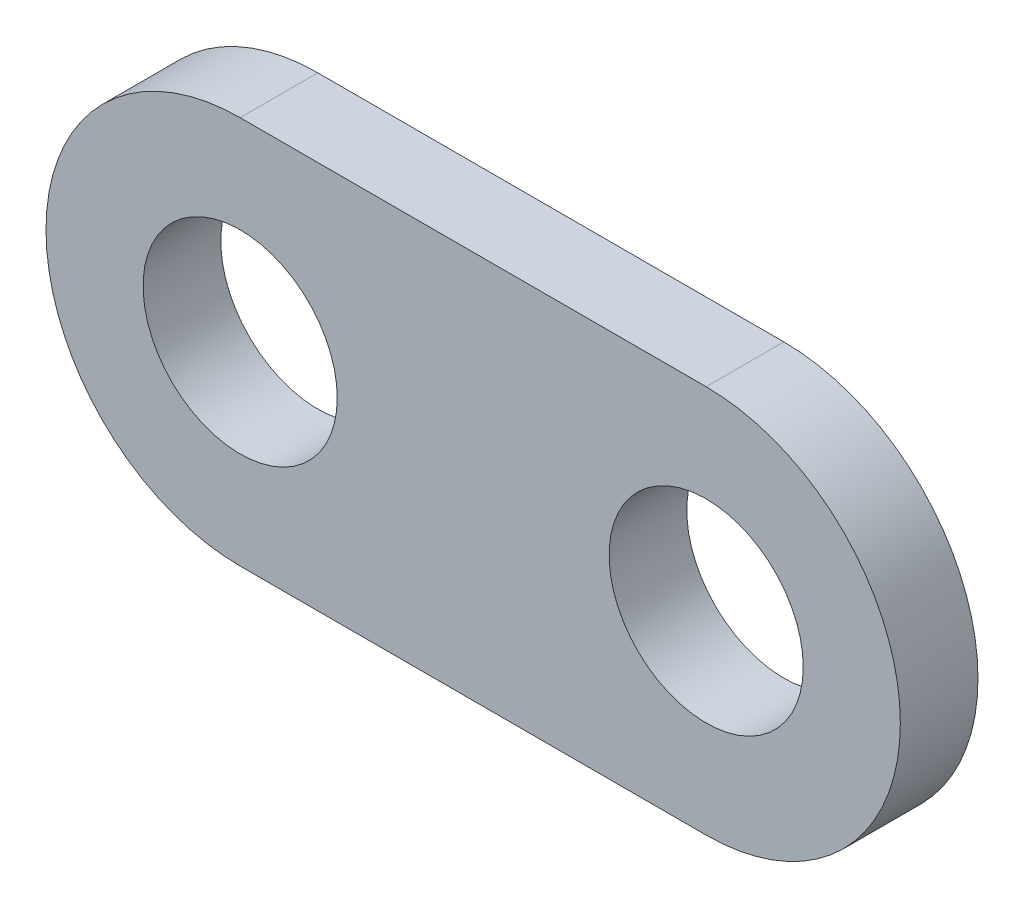
SolidWorks part; units mm, degrees
ref_plane "Plan 1" through (0, 0, 0) normal (0, 0, 1) x (1, 0, 0)
ref_plane "Plan 2" through (0, 0, 0) normal (0, 1, 0) x (1, 0, 0)
ref_plane "Plan 3" through (0, 0, 0) normal (1, 0, 0) x (0, 0, -1)
sketch "Esquisse1" plane through (0, 0, 0) normal (0, 0, 1) x (1, 0, 0)
  line L0 (0, 0) -> (24, 0) construction
  line L1 (0, 10) -> (24, 10)
  line L2 (24, -10) -> (0, -10)
  circle A0 centre (0, 0) radius 5
  circle A1 centre (24, 0) radius 5
  arc A2 (24, 10) -> (24, -10) centre (24, 0) cw
  arc A3 (0, 10) -> (0, -10) centre (0, 0) ccw
  dimension "D1" = 10
  dimension "D2" = 10
  dimension "D3" = 24
extrude "Base-Extrusion" add sketch "Esquisse1" along normal mid plane 4
sketch "Esquisse2" plane through (0, 0, 0) normal (0, 0, 1) x (1, 0, 0)
  point P0 (0, 0)
